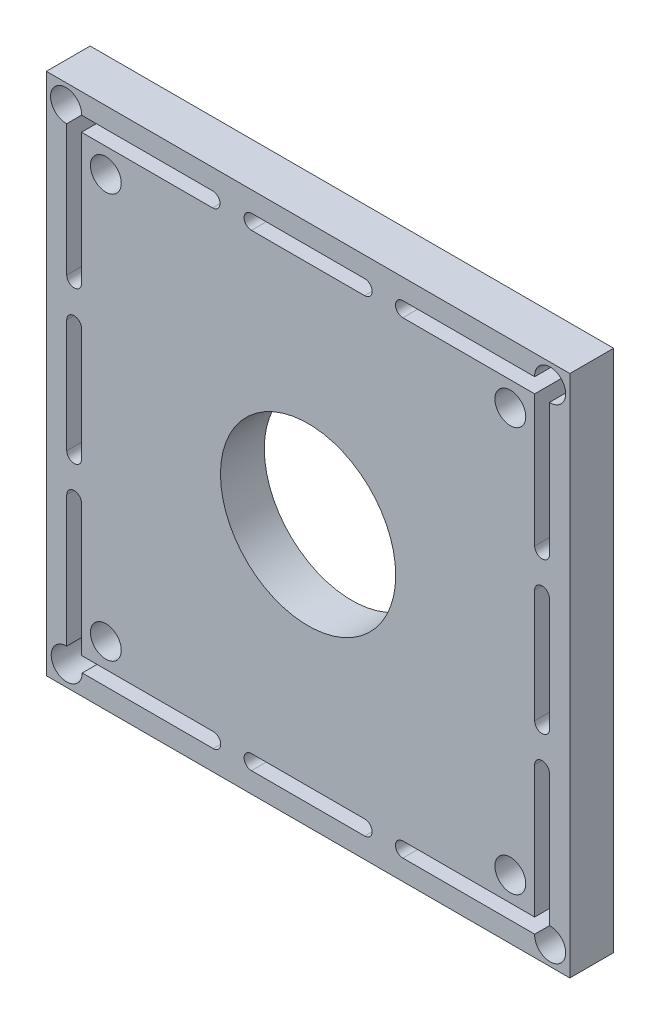
SolidWorks part; units mm, degrees
ref_plane "Front Plane" through (0, 0, 0) normal (0, 0, 1) x (1, 0, 0)
ref_plane "Top Plane" through (0, 0, 0) normal (0, 1, 0) x (1, 0, 0)
ref_plane "Right Plane" through (0, 0, 0) normal (1, 0, 0) x (0, 0, -1)
sketch "Sketch1" plane through (0, 0, 0) normal (0, 0, 1) x (1, 0, 0)
  line L1 (0, 37.9349) -> (37.9349, 37.9349)
  line L2 (0, 37.9349) -> (0, 0)
  line L3 (0, 0) -> (37.9349, 0)
  line L4 (37.9349, 37.9349) -> (37.9349, 0)
  dimension "D1" = 37.9349
extrude "Boss-Extrude1" add sketch "Sketch1" along normal blind 3.175
sketch "Sketch9" plane through (0, 0, 3.175) normal (0, 0, 1) x (1, 0, 0)
  line L0 (33.6232, 33.6232) -> (35.9219, 33.6232) construction
  line L1 (0, 0) -> (37.9349, 0) construction
  line L2 (2.5493, 18.9674) -> (1.4766, 18.9675) construction
  line L3 (33.6232, 35.922) -> (33.6232, 33.6232) construction
  line L4 (0, 37.9349) -> (0, 0) construction
  line L5 (35.3856, 12.1002) -> (36.4583, 12.1002) construction
  line L6 (4.3117, 35.9219) -> (4.3117, 33.6232) construction
  line L7 (2.013, 33.6232) -> (4.3117, 33.6232) construction
  line L8 (4.3117, 2.013) -> (4.3117, 4.3117) construction
  line L9 (2.0129, 4.3117) -> (4.3117, 4.3117) construction
  line L10 (35.9219, 4.3117) -> (33.6232, 4.3117) construction
  line L11 (33.6232, 2.013) -> (33.6232, 4.3117) construction
  line L12 (35.3856, 12.1002) -> (35.3856, 2.5493)
  line L13 (35.3856, 2.5493) -> (25.8347, 2.5493)
  line L14 (35.3856, 1.4766) -> (25.8347, 1.4766)
  line L15 (35.3856, 36.4583) -> (25.8347, 36.4583)
  line L16 (37.9349, 37.9349) -> (0, 37.9349) construction
  line L17 (12.0489, 36.4583) -> (2.5493, 36.4583)
  line L18 (12.0489, 36.4583) -> (12.0489, 35.3856) construction
  line L19 (12.0489, 35.3856) -> (2.5493, 35.3856)
  line L20 (35.922, 35.9219) -> (2.0129, 35.9219) construction
  line L21 (23.0695, 36.4583) -> (14.8653, 36.4583)
  line L22 (35.922, 35.9219) -> (35.922, 2.013) construction
  line L23 (35.922, 2.013) -> (2.013, 2.013) construction
  line L24 (2.0129, 35.9219) -> (2.013, 2.013) construction
  line L25 (18.9674, 37.9349) -> (18.9674, 0) construction
  line L26 (23.0695, 36.4583) -> (23.0695, 35.3856) construction
  line L27 (23.0695, 35.3856) -> (14.8653, 35.3856)
  line L28 (0, 0) -> (37.9349, 0) construction
  line L29 (25.8347, 2.5493) -> (25.8347, 1.4766) construction
  line L30 (14.8653, 36.4583) -> (14.8653, 35.3856) construction
  line L31 (35.3856, 2.5493) -> (36.4583, 2.5493) construction
  line L32 (35.922, 18.9674) -> (2.013, 18.9674) construction
  line L33 (2.5493, 36.4583) -> (2.5493, 35.3856) construction
  line L34 (2.5493, 35.3856) -> (1.4766, 35.3856) construction
  line L35 (2.5493, 12.1002) -> (1.4766, 12.1002) construction
  line L36 (36.4583, 12.1002) -> (36.4583, 2.5493)
  line L37 (35.3856, 35.3856) -> (25.8347, 35.3856)
  line L38 (2.5493, 35.3856) -> (2.5493, 25.886)
  line L39 (12.1002, 2.5493) -> (12.1002, 1.4766) construction
  line L42 (25.8347, 36.4583) -> (25.8347, 35.3856) construction
  line L43 (35.3856, 35.3856) -> (36.4583, 35.3856) construction
  line L44 (35.3856, 35.3856) -> (35.3856, 25.8347)
  line L45 (35.3856, 25.8347) -> (36.4583, 25.8347) construction
  line L46 (36.4583, 35.3856) -> (36.4583, 25.8347)
  line L47 (2.5493, 25.886) -> (1.4766, 25.886) construction
  line L48 (1.4766, 35.3856) -> (1.4766, 25.886)
  line L49 (2.5493, 23.0696) -> (1.4766, 23.0696) construction
  line L50 (2.5493, 23.0696) -> (2.5493, 14.8654)
  line L51 (2.5493, 14.8654) -> (1.4766, 14.8654) construction
  line L52 (1.4766, 23.0696) -> (1.4766, 14.8654)
  line L53 (36.4583, 18.9675) -> (35.3856, 18.9675) construction
  line L54 (36.4583, 23.0695) -> (35.3856, 23.0695) construction
  line L55 (36.4583, 23.0695) -> (36.4583, 14.8654)
  line L56 (36.4583, 14.8654) -> (35.3856, 14.8654) construction
  line L57 (35.3856, 23.0695) -> (35.3856, 14.8654)
  line L58 (18.9674, 36.4583) -> (18.9674, 35.3856) construction
  line L59 (18.9674, 2.5493) -> (18.9674, 1.4766) construction
  line L60 (23.0695, 2.5493) -> (14.8653, 2.5493)
  line L61 (23.0695, 2.5493) -> (23.0695, 1.4766) construction
  line L62 (23.0695, 1.4766) -> (14.8653, 1.4766)
  line L63 (14.8653, 2.5493) -> (14.8653, 1.4766) construction
  line L68 (2.5493, 12.1002) -> (2.5493, 2.5493)
  line L69 (1.4766, 12.1002) -> (1.4766, 2.6006)
  line L70 (2.5493, 2.5493) -> (12.1002, 2.5493)
  line L71 (2.6006, 1.4766) -> (12.1002, 1.4766)
  line L75 (12.1002, 2.013) -> (12.6365, 2.013) construction
  line L76 (2.013, 2.013) -> (2.013, 0) construction
  line L77 (0, 2.0129) -> (2.013, 2.013) construction
  circle A0 centre (33.6232, 33.6232) radius 1.1176
  circle A1 centre (4.3117, 33.6232) radius 1.1176
  circle A2 centre (4.3117, 4.3117) radius 1.1176
  circle A3 centre (33.6232, 4.3117) radius 1.1176
  arc A4 (25.8347, 1.4766) -> (25.8347, 2.5493) centre (25.8347, 2.013) cw
  arc A5 (36.4583, 2.5493) -> (35.3856, 1.4766) centre (36.5084, 1.4265) cw
  arc A6 (14.8653, 36.4583) -> (14.8653, 35.3856) centre (14.8653, 35.9219) ccw
  arc A7 (23.0695, 36.4583) -> (23.0695, 35.3856) centre (23.0695, 35.9219) cw
  arc A8 (1.4766, 2.6006) -> (2.6006, 1.4766) centre (1.4766, 1.4766) ccw
  arc A9 (36.4583, 12.1002) -> (35.3856, 12.1002) centre (35.9219, 12.1002) ccw
  arc A10 (12.0489, 35.3856) -> (12.0489, 36.4583) centre (12.0489, 35.9219) ccw
  arc A11 (1.4766, 35.3856) -> (2.5493, 36.4583) centre (1.4265, 36.5084) cw
  arc A12 (36.4583, 25.8347) -> (35.3856, 25.8347) centre (35.922, 25.8347) cw
  arc A13 (25.8347, 35.3856) -> (25.8347, 36.4583) centre (25.8347, 35.9219) cw
  arc A14 (36.4583, 35.3856) -> (35.3856, 36.4583) centre (36.5084, 36.5084) ccw
  arc A15 (2.5493, 25.886) -> (1.4766, 25.886) centre (2.013, 25.886) cw
  arc A16 (2.5493, 23.0696) -> (1.4766, 23.0696) centre (2.0129, 23.0695) ccw
  arc A17 (1.4766, 14.8654) -> (2.5493, 14.8654) centre (2.0129, 14.8654) ccw
  arc A18 (1.4766, 12.1002) -> (2.5493, 12.1002) centre (2.0129, 12.1002) cw
  arc A19 (12.1002, 2.5493) -> (12.1002, 1.4766) centre (12.1002, 2.013) cw
  arc A20 (36.4583, 23.0695) -> (35.3856, 23.0695) centre (35.922, 23.0695) ccw
  arc A21 (36.4583, 14.8654) -> (35.3856, 14.8654) centre (35.922, 14.8653) cw
  arc A22 (14.8653, 2.5493) -> (14.8653, 1.4766) centre (14.8654, 2.0129) ccw
  arc A23 (23.0695, 1.4766) -> (23.0695, 2.5493) centre (23.0695, 2.0129) ccw
  circle A24 centre (18.9674, 18.9674) radius 6.35
  point P47 (18.9674, 18.9674)
  point P66 (2.0129, 18.9674)
  point P89 (35.922, 18.9674)
  dimension "D1" = 9.4996
  dimension "D3" = 2.013
  dimension "D4" = 2.2352
  dimension "D6" = 8.2042
  dimension "D5" = 1.1239
  dimension "D7" = 1.0727
  dimension "D8" = 12.7
  dimension "D2" = 2.2987
extrude "Cut-Extrude2" cut sketch "Sketch9" against normal up to surface (3.175 mm away) up to face at (18.9674, 18.9675, 0)
